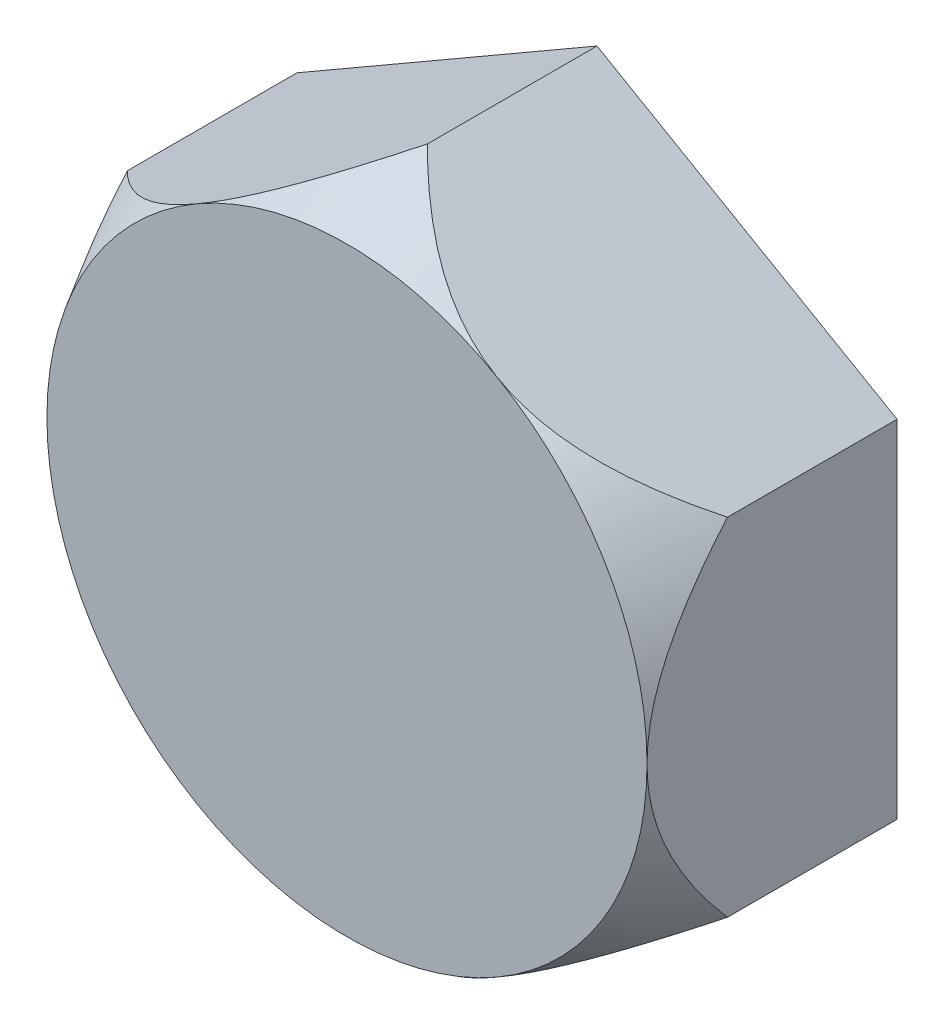
SolidWorks part; units mm, degrees
ref_plane "Front Plane" through (0, 0, 0) normal (0, 0, 1) x (1, 0, 0)
ref_plane "Top Plane" through (0, 0, 0) normal (0, 1, 0) x (1, 0, 0)
ref_plane "Right Plane" through (0, 0, 0) normal (1, 0, 0) x (0, 0, -1)
sketch "Sketch1" plane through (0, 0, 0) normal (0, 0, 1) x (1, 0, 0)
  line L1 (0, -34.64) -> (29.9991, -17.32)
  line L2 (29.9991, -17.32) -> (29.9991, 17.32)
  line L3 (29.9991, 17.32) -> (0, 34.64)
  line L4 (0, 34.64) -> (-29.9991, 17.32)
  line L5 (-29.9991, 17.32) -> (-29.9991, -17.32)
  line L6 (-29.9991, -17.32) -> (0, -34.64)
  circle A0 centre (0, 0) radius 29.9991 construction
  point P1 (0, 0)
  dimension "D1" = 69.28
  dimension "D2" = 59.9982
extrude "Boss-Extrude1" add sketch "Sketch1" along normal blind 25
sketch "Sketch2" plane through (0, 0, 25) normal (0, 0, 1) x (1, 0, 0)
  line L0 (-29.9991, 17.32) -> (-29.9991, -17.32) construction
  circle A0 centre (0, 0) radius 29.9991
  point P5 (0, 0)
extrude "Cut-Extrude2" cut sketch "Sketch2" against normal through all draft 30 flip side to cut contours A0
